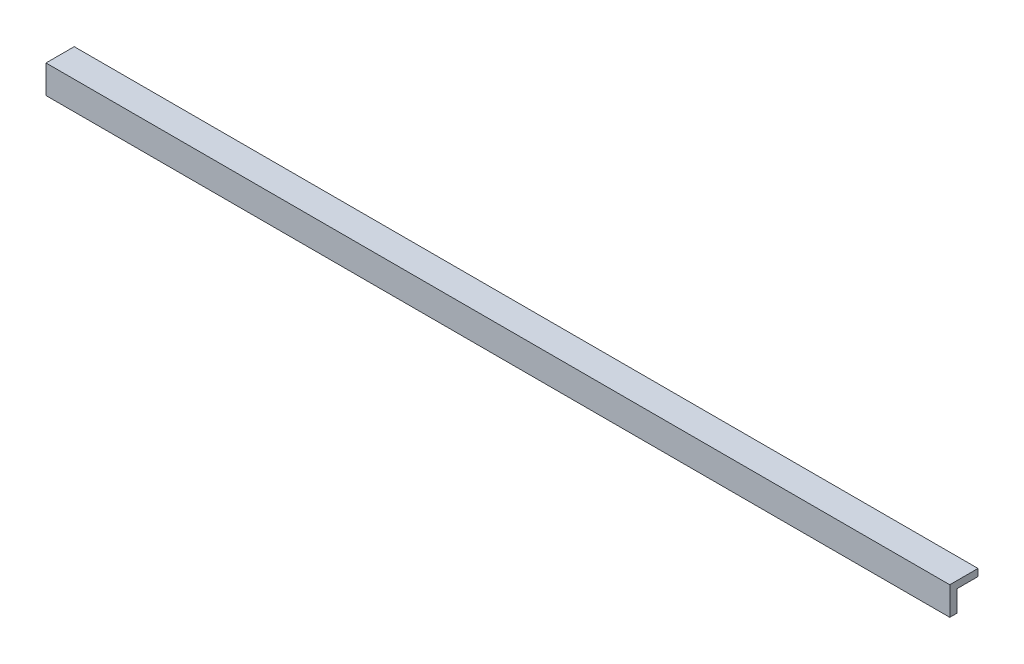
SolidWorks part; units mm, degrees
material "1060 Alloy"
ref_plane "Front Plane" through (0, 0, 0) normal (0, 0, 1) x (1, 0, 0)
ref_plane "Top Plane" through (0, 0, 0) normal (0, 1, 0) x (1, 0, 0)
ref_plane "Right Plane" through (0, 0, 0) normal (1, 0, 0) x (0, 0, -1)
sketch "Sketch1" plane through (0, 0, 0) normal (1, 0, 0) x (0, 0, -1)
  line L0 (0, 0) -> (0, 6.35)
  line L1 (0, 6.35) -> (6.35, 6.35)
  line L2 (6.35, 6.35) -> (6.35, 4.7625)
  line L3 (6.35, 4.7625) -> (1.5875, 4.7625)
  line L4 (1.5875, 4.7625) -> (1.5875, 0)
  line L5 (1.5875, 0) -> (0, 0)
  dimension "D1" = 6.35
  dimension "D2" = 6.35
  dimension "D3" = 1.5875
  dimension "D4" = 1.5875
extrude "Boss-Extrude1" add sketch "Sketch1" along normal blind 203.2
